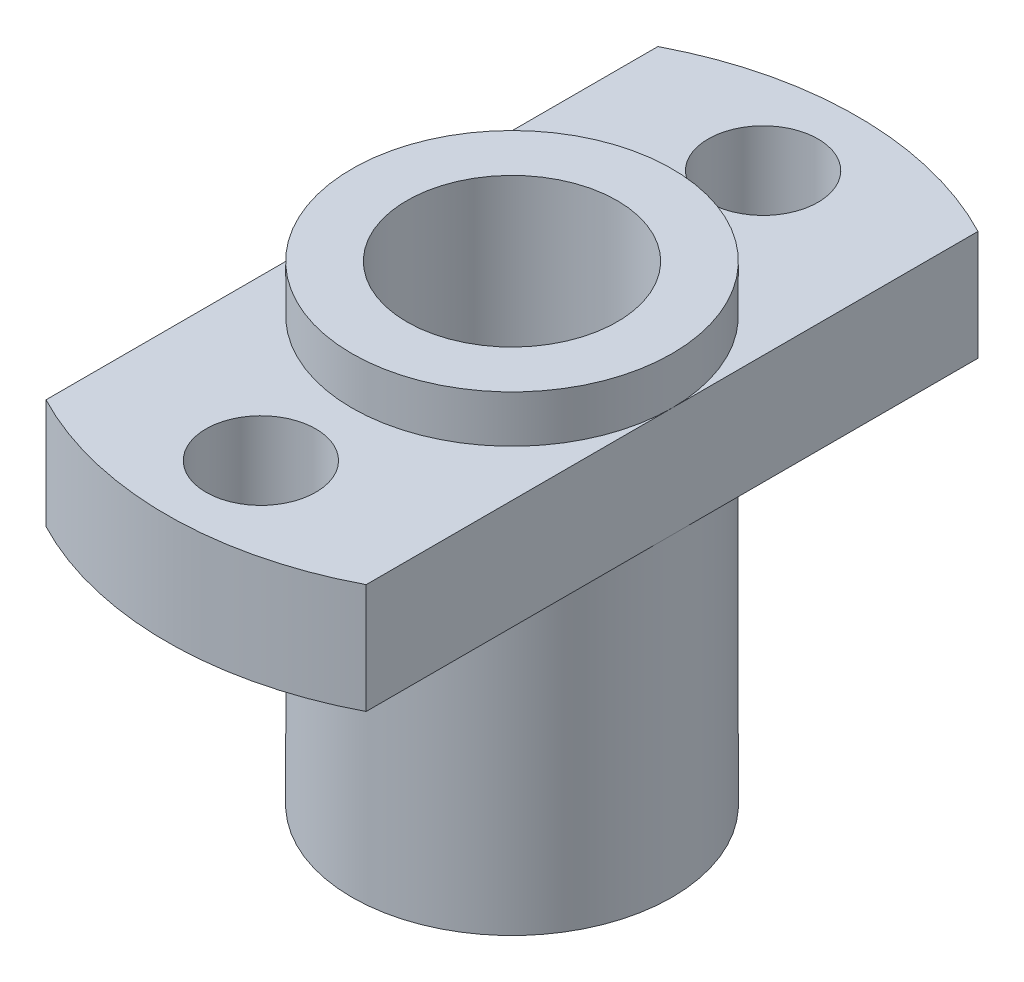
SolidWorks part; units mm, degrees
material "Brass"
ref_plane "Front Plane" through (0, 0, 0) normal (0, 0, 1) x (1, 0, 0)
ref_plane "Top Plane" through (0, 0, 0) normal (0, 1, 0) x (1, 0, 0)
ref_plane "Right Plane" through (0, 0, 0) normal (1, 0, 0) x (0, 0, -1)
sketch "Sketch1" plane through (0, 0, 0) normal (0, 1, 0) x (1, 0, 0)
  circle A0 centre (0, 0) radius 5.1
  dimension "D1" = 10.2
extrude "Boss-Extrude1" add sketch "Sketch1" along normal blind 15
ref_plane "Plane1" through (0, 13.5, 0) normal (0, 1, 0) x (1, 0, 0)
sketch "Sketch2" plane through (0, 13.5, 0) normal (0, 1, 0) x (1, 0, 0)
  line L0 (0, 15.121) -> (0, -19.4958) construction
  line L1 (-19.3321, 0) -> (21.8104, 0) construction
  line L2 (-5.1, 9.7463) -> (-5.1, -9.7463)
  line L3 (5.1, 9.7463) -> (5.1, -9.7463)
  line L4 (-19.3321, -8) -> (21.8104, -8) construction
  line L5 (-5.1, 15.121) -> (-5.1, -19.4958) construction
  line L6 (5.1, 15.121) -> (5.1, -19.4958) construction
  line L7 (-19.3321, 8) -> (21.8104, 8) construction
  arc A0 (-5.1, -9.7463) -> (5.1, -9.7463) centre (0, 0) ccw
  arc A1 (5.1, 9.7463) -> (-5.1, 9.7463) centre (0, 0) ccw
  circle A2 centre (0, 8) radius 1.75
  circle A3 centre (0, -8) radius 1.75
  point P22 (0, -8)
  dimension "D1" = 22
  dimension "D6" = 3.5
  dimension "D7" = 3.5
  dimension "D2" = 5.1
  dimension "D3" = 5.1
  dimension "D4" = 8
  dimension "D5" = 8
extrude "Boss-Extrude2" add sketch "Sketch2" against normal blind 3.5
sketch "Sketch3" plane through (0, 15, 0) normal (0, 1, 0) x (1, 0, 0)
  circle A0 centre (0, 0) radius 3.35
  dimension "D1" = 6.7
extrude "Cut-Extrude1" cut sketch "Sketch3" against normal through all
cosmetic thread "Cosmetic Thread1" parameters "D2"=8
